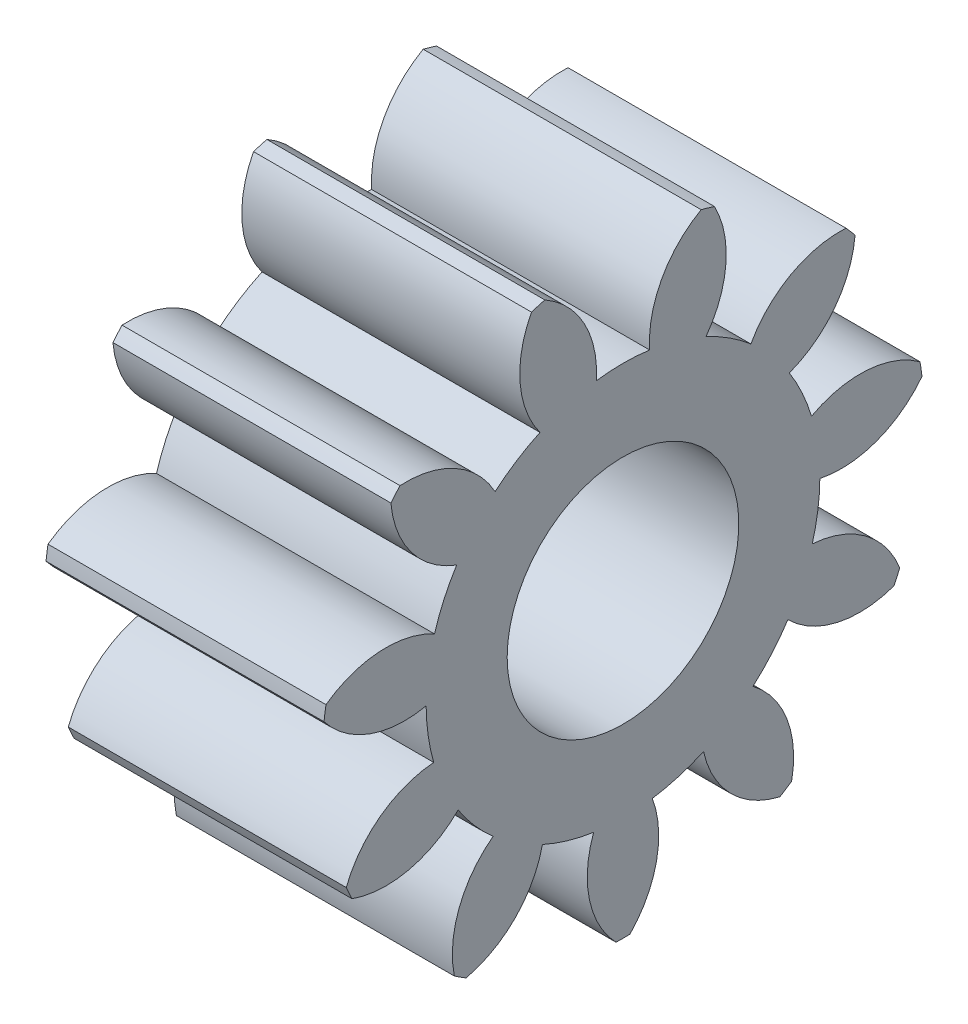
SolidWorks part; units mm, degrees
ref_plane "Plane1" through (0, 0, 0) normal (0, 0, 1) x (1, 0, 0)
ref_plane "Plane2" through (0, 0, 0) normal (0, 1, 0) x (1, 0, 0)
ref_plane "Plane3" through (0, 0, 0) normal (1, 0, 0) x (0, 0, -1)
other "Configuration Table"
sketch "HoldingSke" plane through (0, 0, 0) normal (0, 1, 0) x (1, 0, 0)
  line L0 (0, 0) -> (0.9848, -0.1736)
  line L1 (-15, 0) -> (100, 0) construction
  line L2 (0, 0) -> (-2.1039, 2.3779)
  line L3 (0, 0) -> (-11.863, 4.5341)
  line L4 (0, 0) -> (8.4773, 1.6478)
  line L5 (0, 0) -> (-46.8476, -17.4728)
  line L6 (0, 0) -> (-4.9738, -3.3558)
  line L7 (-2.1039, 2.3779) -> (8.6586, 51.2059)
  line L8 (-76.2, 54.61) -> (-75.3, 54.61)
  line L9 (-71.009, 38.7566) -> (-53.1078, 45.2721)
  line L10 (-76.2, 71.12) -> (104.1128, 71.12)
  line L11 (0, 0) -> (-6, 0)
  line L12 (-76.2, 101.6) -> (-76.162, 101.6)
  line L13 (24.9733, 27.94) -> (52.9518, 28.4284)
  line L14 (24.9733, 27.94) -> (24.9743, 27.94)
  line L15 (24.9733, 27.94) -> (100.4006, 29.5858)
  line L16 (-63.627, -1) -> (-12.827, -1)
  circle A0 centre (0, 0) radius 2.5
  circle A1 centre (0, 0) radius 4.249
  circle A2 centre (0, 0) radius 37.5
  circle A3 centre (0, 0) radius 2.5
  dimension "MHD" = 8.498
  dimension "Hub_dia" = 75
  dimension "Bore" = 5
  dimension "MBD" = 5
  dimension "Num_teeth" = 11
  dimension "Pitch" = 1
  dimension "Overall_len" = 50
  dimension "Show_teeth" = 10
  dimension "Thickness" = 6
  dimension "OAL" = 50.0001
  dimension "T_dim" = 0.9
  dimension "Ap" = 20
  dimension "H" = 19.05
  dimension "Pitch_radius" = 180.3128
  dimension "Width" = 6
  dimension "Backlash" = 0.038
  dimension "Addendum_fac" = 1
  dimension "Dedendum_fac" = 1.25
  dimension "Clearance_fac" = 0.25
  dimension "Dedendum_add" = 0.001
  dimension "Module" = 1
sketch "BasProSke" plane through (0, 0, 0) normal (0, 1, 0) x (1, 0, 0)
  line L0 (-10, 0) -> (60, 0) construction
  line L1 (0, 0) -> (0, 6.5)
  line L2 (0, 0) -> (6, 0)
  line L3 (6, 0) -> (6, 6.5)
  line L4 (6, 6.5) -> (0, 6.5)
  dimension "Thickness" = 6
  dimension "Diameter" = 13
revolve "Base-Revolve" add sketch "BasProSke" angle 360 about L0
sketch "TooCutSke" plane through (0, 0, 0) normal (1, 0, 0) x (0, 0, -1)
  line L1 (0, 0) -> (0, 107) construction
  line L2 (0, 0) -> (-0.8491, 5.4341) construction
  line L3 (0, 0) -> (-3.0727, 10.4645) construction
  line L4 (-0.8491, 5.4341) -> (-1.5363, 5.2323) construction
  arc A0 (0.576, 4.2098) -> (-0.576, 4.2098) centre (0, 0) ccw
  arc A1 (1.7187, 6.295) -> (-1.7187, 6.295) centre (0, 0) ccw
  circle A2 centre (0, 0) radius 5.5 construction
  circle A3 centre (0, 0) radius 5.1683 construction
  arc A4 (-0.576, 4.2098) -> (-1.7187, 6.295) centre (-2.7707, 4.3629) ccw
  arc A5 (1.7187, 6.295) -> (0.576, 4.2098) centre (2.7707, 4.3629) ccw
  dimension "Root_dia" = 8.498
  dimension "Overcut_dia" = 13.0508
  dimension "Pitch_dia" = 11
  dimension "Base_dia" = 10.3366
  dimension "Flank_rad" = 2.2
  dimension "Half_ang" = 16.364
  dimension "Half_CT" = 0.7162
extrude "ToothCut" cut sketch "TooCutSke" along normal through all
fillet "Breaks" [suppressed] radius 0.02
fillet "RootFillets" [suppressed] radius 0.251
pattern_circular "TeethCuts" count 11 every 32.727 about axis through (-10, 0, 0) along (1, 0, 0) of "ToothCut", "RootFillets", "Breaks"
sketch "HubNeaOneSke" plane through (0, 0, 0) normal (-1, 0, 0) x (0, 0, 1)
  circle A0 centre (0, 0) radius 4.249
  dimension "Diameter" = 8.498
extrude "HubNearOne" [suppressed] add sketch "HubNeaOneSke" along normal blind 44.0001
sketch "HubNeaBotSke" plane through (0, 0, 0) normal (-1, 0, 0) x (0, 0, 1)
  circle A0 centre (0, 0) radius 4.249
  dimension "Diameter" = 8.498
extrude "HubNearBoth" [suppressed] add sketch "HubNeaBotSke" along normal blind 22
ref_plane "FarPln" through (6, 0, 0) normal (1, 0, 0) x (0, 0, -1)
sketch "HubFarSke" plane through (6, 0, 0) normal (1, 0, 0) x (0, 0, -1)
  circle A0 centre (0, 0) radius 4.249
  dimension "Diameter" = 8.498
extrude "HubFar" [suppressed] add sketch "HubFarSke" along normal blind 22
sketch "BorSke" plane through (0, 0, 0) normal (1, 0, 0) x (0, 0, -1)
  circle A0 centre (0, 0) radius 2.5
  dimension "Diameter" = 5
extrude "Bore" cut sketch "BorSke" along normal mid plane 100.0001
sketch "KeySke" plane through (0, 0, 0) normal (1, 0, 0) x (0, 0, -1)
  line L0 (-1, 0) -> (-1, 3.4)
  line L1 (-1, 3.4) -> (1, 3.4)
  line L2 (1, 3.4) -> (1, 0)
  line L3 (0, 0) -> (0, 34) construction
  line L4 (-1, 0) -> (1, 0)
  dimension "Offset" = 3.4
  dimension "Width" = 2
extrude "Keyway" [suppressed] cut sketch "KeySke" along normal mid plane 100.0001
pattern_circular "Keyway2" [suppressed] count 2 every 90 about axis through (-10, 0, 0) along (1, 0, 0)
equation "' \"Module@HoldingSke\" = 6.35"
equation "' \"Num_teeth@HoldingSke\" = 12"
equation "' \"Ap@HoldingSke\" =  20"
equation "' \"Ap@HoldingSke\" = 20"
equation "' \"Width@HoldingSke\" = 0.5 * 25.4"
equation "' \"Hub_dia@HoldingSke\"= 1 * 25.4"
equation "' \"Hub_dia@HoldingSke\" = 1 * 25.4"
equation "' \"Overall_len@HoldingSke\" = 1.0 * 25.4"
equation "' \"Bore@HoldingSke\" = 0.75 * 25.4"
equation "' \"T_dim@HoldingSke\" = 0.1 * 25.4"
equation "' \"Width@KeySke\" = 0.25 * 25.4"
equation "' \"Show_teeth@HoldingSke\" = 13"
equation "' \"Backlash@HoldingSke\" = 0.009 * 25.4"
equation "' \"Addendum_fac@HoldingSke\" = 1.0"
equation "' \"Dedendum_fac@HoldingSke\" = 1.25"
equation "' \"Dedendum_add@HoldingSke\" = 0.00005 * 25.4"
equation "' \"Clearance_fac@HoldingSke\" = 0.25"
equation "\"Pitch@HoldingSke\" = 1 / \"Module@HoldingSke\""
equation "\"Overcut_dia@TooCutSke\" = (\"Num_teeth@HoldingSke\" + 2 * \"Addendum_fac@HoldingSke\") / \"Pitch@HoldingSke\" + 0.002 * 25.4"
equation "\"Pitch_dia@TooCutSke\" = \"Num_teeth@HoldingSke\" / \"Pitch@HoldingSke\""
equation "\"Base_dia@TooCutSke\" = \"Num_teeth@HoldingSke\" / \"Pitch@HoldingSke\" * cos((\"Ap@HoldingSke\"  * 3.14159265 / 180))"
equation "\"Root_dia@TooCutSke\" = (\"Num_teeth@HoldingSke\" + 2) / \"Pitch@HoldingSke\" - 2 * (\"Addendum_fac@HoldingSke\" + \"Dedendum_fac@HoldingSke\") / \"Pitch@HoldingSke\" - \"Dedendum_add@HoldingSke\" * 2"
equation "\"Half_ang@TooCutSke\" = 180 / \"Num_teeth@HoldingSke\""
equation "\"Half_CT@TooCutSke\" = \"Num_teeth@HoldingSke\" / \"Pitch@HoldingSke\" * sin((3.14159265 / 2 / \"Num_teeth@HoldingSke\")) / 2 - 7 * \"Backlash@HoldingSke\" / 4"
equation "\"Flank_rad@TooCutSke\" = \"Num_teeth@HoldingSke\" / \"Pitch@HoldingSke\" / 5"
equation "\"Radius@RootFillets\" = \"Clearance_fac@HoldingSke\" / \"Pitch@HoldingSke\" + \"Dedendum_add@HoldingSke\""
equation "\"Break_rad@Breaks\" = 0.02 / \"Pitch@HoldingSke\""
equation "\"Thickness@HoldingSke\" = \"Width@HoldingSke\""
equation "\"OAL@HoldingSke\" = \"Thickness@HoldingSke\""
equation "\"MHD@HoldingSke\" = (\"Num_teeth@HoldingSke\" + 2) / \"Pitch@HoldingSke\" - 2 * (\"Addendum_fac@HoldingSke\" + \"Dedendum_fac@HoldingSke\")  / \"Pitch@HoldingSke\" - \"Dedendum_add@HoldingSke\" * 2"
equation "\"MBD@HoldingSke\" = (\"Num_teeth@HoldingSke\" + 2) / \"Pitch@HoldingSke\" - 2 * (\"Addendum_fac@HoldingSke\" + \"Dedendum_fac@HoldingSke\")  / \"Pitch@HoldingSke\" - \"Dedendum_add@HoldingSke\" * 2 - 0.002 * 25.4"
equation "\"MHD@HoldingSke\" = ((sgn( \"MHD@HoldingSke\" - \"Hub_dia@HoldingSke\" )-1)*( \"MHD@HoldingSke\" - \"Hub_dia@HoldingSke\" ))/-2+ \"Hub_dia@HoldingSke\""
equation "\"MBD@HoldingSke\" = ((sgn( \"MBD@HoldingSke\" - \"Bore@HoldingSke\" )-1)*( \"MBD@HoldingSke\" - \"Bore@HoldingSke\" ))/-2+ \"Bore@HoldingSke\""
equation "\"OAL@HoldingSke\" = ((sgn( \"OAL@HoldingSke\" - \"Overall_len@HoldingSke\" )+1)*( \"OAL@HoldingSke\" - \"Overall_len@HoldingSke\" ))/2 + \"Overall_len@HoldingSke\" + 0.000002 * 25.4"
equation "\"Num_teeth@TeethCuts\" = int( \"Show_teeth@HoldingSke\" ) + 1"
equation "\"Num_teeth@TeethCuts\" = ((sgn( \"Num_teeth@TeethCuts\" - \"Num_teeth@HoldingSke\" )-1)*( \"Num_teeth@TeethCuts\" - \"Num_teeth@HoldingSke\" ))/-2+ \"Num_teeth@HoldingSke\""
equation "\"Num_teeth@TeethCuts\" = ((sgn( \"Num_teeth@TeethCuts\" - 2.0)+1)*( \"Num_teeth@TeethCuts\" - 2.0))/2 +2.0"
equation "\"Angle@TeethCuts\" = 360.0 / \"Num_teeth@HoldingSke\""
equation "\"Diameter@BasProSke\" = (\"Num_teeth@HoldingSke\" + 2 * \"Addendum_fac@HoldingSke\") / \"Pitch@HoldingSke\""
equation "\"Thickness@BasProSke\"  = \"Thickness@HoldingSke\""
equation "' \"Fillet_rad@BasProSke\" =  \"Thickness@HoldingSke\" * 0.05"
equation "' \"Fillet_rad@BasProSke\" = \"Thickness@HoldingSke\" * 0.05"
equation "\"MHD@HoldingSke\" = ((sgn( \"MHD@HoldingSke\" - \"Root_dia@TooCutSke\" )-1)*( \"MHD@HoldingSke\" - \"Root_dia@TooCutSke\" ))/-2+ \"Root_dia@TooCutSke\""
equation "\"Diameter@HubNeaOneSke\" = \"MHD@HoldingSke\""
equation "\"Length@HubNearOne\" = \"OAL@HoldingSke\" - \"Thickness@BasProSke\""
equation "\"Diameter@HubNeaBotSke\" = \"MHD@HoldingSke\""
equation "\"Length@HubNearBoth\" = ( \"OAL@HoldingSke\" - \"Thickness@BasProSke\" ) / 2.0"
equation "\"Thickness@FarPln\" = \"Thickness@BasProSke\""
equation "\"Diameter@HubFarSke\" = \"MHD@HoldingSke\""
equation "\"Length@HubFar\" = ( \"OAL@HoldingSke\" - \"Thickness@BasProSke\" ) / 2.0"
equation "\"Diameter@BorSke\" = \"MBD@HoldingSke\""
equation "\"D1@Bore\" = \"OAL@HoldingSke\" * 2.0"
equation "\"D1@Keyway\" = \"OAL@HoldingSke\" * 2.0"
equation "\"Offset@KeySke\" = \"T_dim@HoldingSke\" + \"MBD@HoldingSke\" / 2.0"
